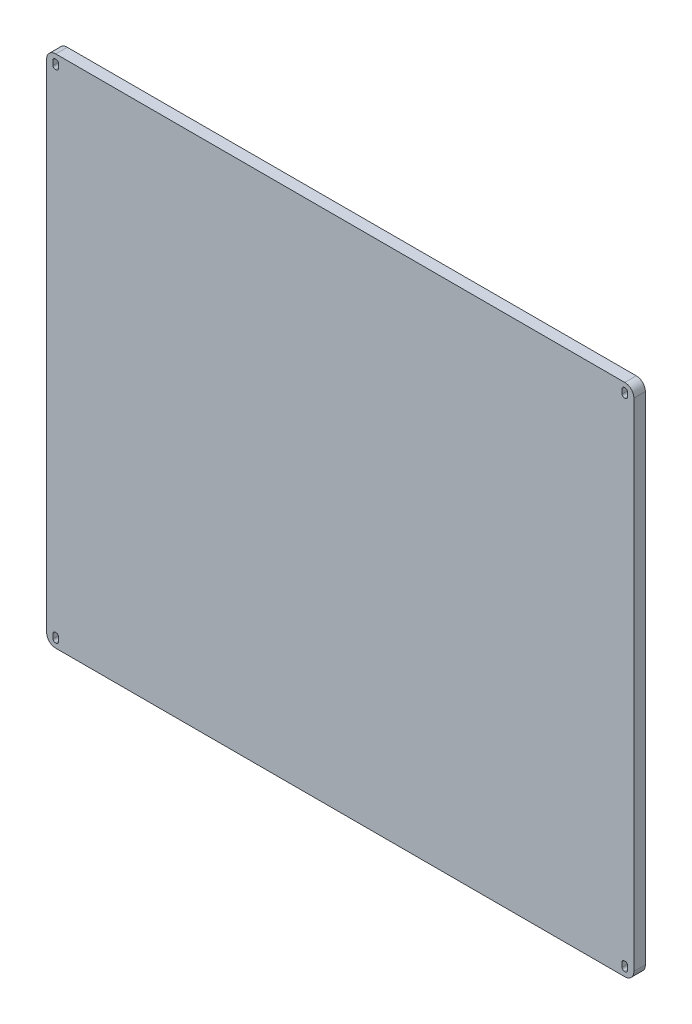
SolidWorks part; units mm, degrees
ref_plane "Front Plane" through (0, 0, 0) normal (0, 0, 1) x (1, 0, 0)
ref_plane "Top Plane" through (0, 0, 0) normal (0, 1, 0) x (1, 0, 0)
ref_plane "Right Plane" through (0, 0, 0) normal (1, 0, 0) x (0, 0, -1)
sketch "Sketch1" plane through (0, 0, 0) normal (0, 0, 1) x (1, 0, 0)
  line L0 (300.2523, -434.9172) -> (299.2523, -434.9172)
  line L1 (-337.9477, 127.7728) -> (309.7523, 127.7728)
  line L2 (-337.9477, 127.7728) -> (-337.9477, -439.9172)
  line L3 (-337.9477, -439.9172) -> (309.7523, -439.9172)
  line L4 (309.7523, 127.7728) -> (309.7523, -439.9172)
  line L5 (302.7523, -432.4172) -> (302.7523, -427.4172)
  line L6 (300.2523, -424.9172) -> (299.2523, -424.9172)
  line L7 (296.7523, -432.4172) -> (296.7523, -427.4172)
  line L8 (299.7523, -424.9172) -> (299.7523, -434.9172) construction
  line L9 (296.7523, -429.9172) -> (302.7523, -429.9172) construction
  line L10 (-327.4477, -434.9172) -> (-328.4477, -434.9172)
  line L11 (-330.9477, -432.4172) -> (-330.9477, -427.4172)
  line L12 (-327.4477, -424.9172) -> (-328.4477, -424.9172)
  line L13 (-324.9477, -432.4172) -> (-324.9477, -427.4172)
  line L14 (-327.4477, 112.7728) -> (-328.4477, 112.7728)
  line L15 (-330.9477, 115.2728) -> (-330.9477, 120.2728)
  line L16 (-327.4477, 122.7728) -> (-328.4477, 122.7728)
  line L17 (-324.9477, 115.2728) -> (-324.9477, 120.2728)
  line L18 (300.2523, 112.7728) -> (299.2523, 112.7728)
  line L19 (296.7523, 115.2728) -> (296.7523, 120.2728)
  line L20 (300.2523, 122.7728) -> (299.2523, 122.7728)
  line L21 (302.7523, 115.2728) -> (302.7523, 120.2728)
  arc A0 (300.2523, -434.9172) -> (302.7523, -432.4172) centre (300.2523, -432.4172) ccw
  arc A1 (302.7523, -427.4172) -> (300.2523, -424.9172) centre (300.2523, -427.4172) ccw
  arc A2 (299.2523, -434.9172) -> (296.7523, -432.4172) centre (299.2523, -432.4172) cw
  arc A3 (299.2523, -424.9172) -> (296.7523, -427.4172) centre (299.2523, -427.4172) ccw
  arc A4 (-328.4477, -434.9172) -> (-330.9477, -432.4172) centre (-328.4477, -432.4172) cw
  arc A5 (-328.4477, -424.9172) -> (-330.9477, -427.4172) centre (-328.4477, -427.4172) ccw
  arc A6 (-324.9477, -427.4172) -> (-327.4477, -424.9172) centre (-327.4477, -427.4172) ccw
  arc A7 (-327.4477, -434.9172) -> (-324.9477, -432.4172) centre (-327.4477, -432.4172) ccw
  arc A8 (-328.4477, 112.7728) -> (-330.9477, 115.2728) centre (-328.4477, 115.2728) cw
  arc A9 (-328.4477, 122.7728) -> (-330.9477, 120.2728) centre (-328.4477, 120.2728) ccw
  arc A10 (-324.9477, 120.2728) -> (-327.4477, 122.7728) centre (-327.4477, 120.2728) ccw
  arc A11 (-327.4477, 112.7728) -> (-324.9477, 115.2728) centre (-327.4477, 115.2728) ccw
  arc A12 (299.2523, 112.7728) -> (296.7523, 115.2728) centre (299.2523, 115.2728) cw
  arc A13 (299.2523, 122.7728) -> (296.7523, 120.2728) centre (299.2523, 120.2728) ccw
  arc A14 (302.7523, 120.2728) -> (300.2523, 122.7728) centre (300.2523, 120.2728) ccw
  arc A15 (300.2523, 112.7728) -> (302.7523, 115.2728) centre (300.2523, 115.2728) ccw
  dimension "D5" = 2.5
  dimension "D1" = 647.7
  dimension "D2" = 567.69
  dimension "D3" = 10
  dimension "D4" = 6
  dimension "D6" = 127.7728
  dimension "D7" = 309.7523
  dimension "D8" = 10
  dimension "D9" = 10
  dimension "D12" = 7
  dimension "D13" = 5
  dimension "D14" = 7
  dimension "D10" = 2
  dimension "D11" = 2
extrude "Boss-Extrude1" add sketch "Sketch1" along normal blind 12.7 contours L1 L4 L3 L2 | L14 A8 L15 A9 L16 A10 L17 A11 | L18 A12 L19 A13 L20 A14 L21 A15 | L0 A2 L7 A3 L6 A1 L5 A0 | L10 A4 L11 A5 L12 A6 L13 A7
fillet "Fillet1" radius 10 4 edges at (-337.9477, -439.9172, 6.35) (309.7523, -439.9172, 6.35) (-337.9477, 127.7728, 6.35) (309.7523, 127.7728, 6.35)
